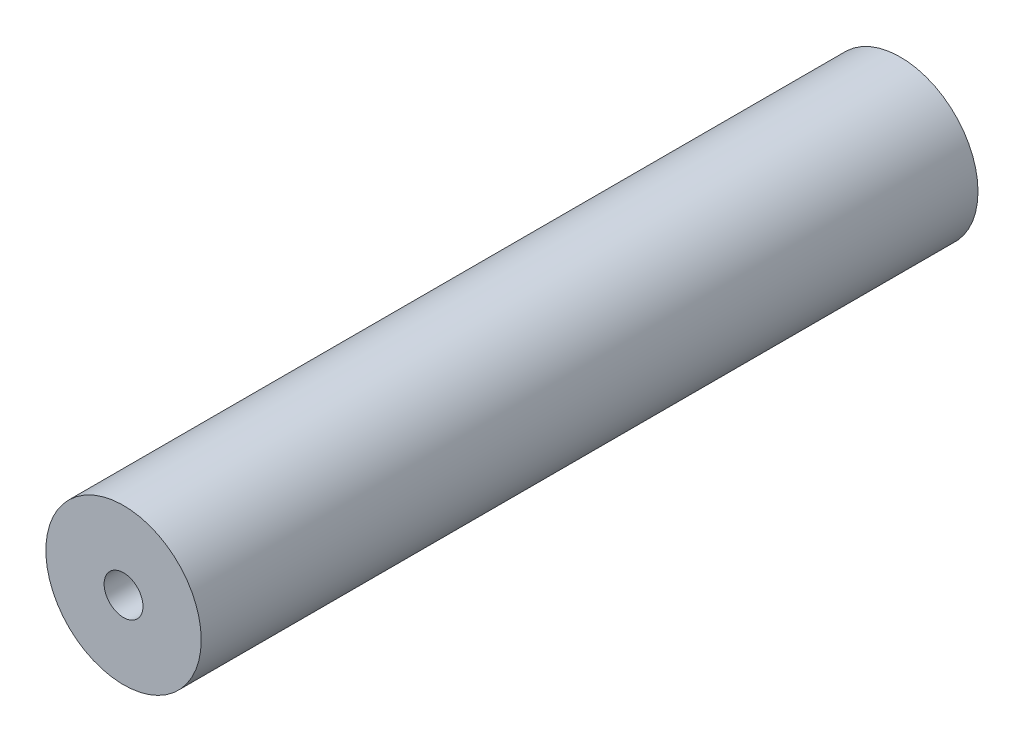
SolidWorks part; units mm, degrees
material "Plain Carbon Steel"
ref_plane "Front Plane" through (0, 0, 0) normal (0, 0, 1) x (1, 0, 0)
ref_plane "Top Plane" through (0, 0, 0) normal (0, 1, 0) x (1, 0, 0)
ref_plane "Right Plane" through (0, 0, 0) normal (1, 0, 0) x (0, 0, -1)
sketch "Sketch1" plane through (0, 0, 0) normal (0, 0, 1) x (1, 0, 0)
  circle A0 centre (0, 0) radius 40
  dimension "D1" = 80
extrude "Boss-Extrude1" add sketch "Sketch1" along normal mid plane 400
sketch "Sketch2" plane through (0, 0, 200) normal (0, 0, 1) x (1, 0, 0)
  circle A0 centre (0, 0) radius 10
  dimension "D1" = 20
extrude "Cut-Extrude1" cut sketch "Sketch2" against normal blind 120
sketch "Sketch3" plane through (0, 0, -200) normal (0, 0, -1) x (-1, 0, 0)
  circle A0 centre (0, 0) radius 10
  dimension "D1" = 20
extrude "Cut-Extrude2" cut sketch "Sketch3" against normal blind 120
